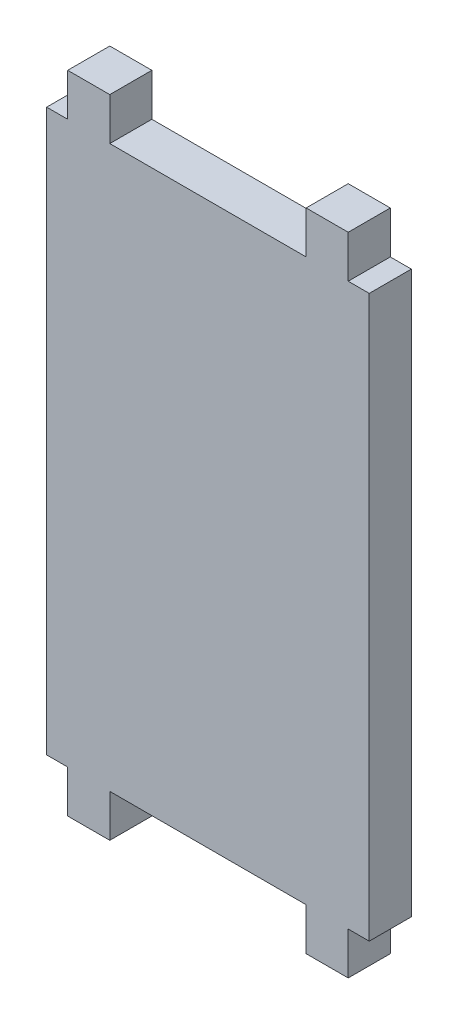
SolidWorks part; units mm, degrees
ref_plane "Alzado" through (0, 0, 0) normal (0, 0, 1) x (1, 0, 0)
ref_plane "Planta" through (0, 0, 0) normal (0, 1, 0) x (1, 0, 0)
ref_plane "Vista lateral" through (0, 0, 0) normal (1, 0, 0) x (0, 0, -1)
sketch "Model" plane through (0, 0, 0) normal (0, 0, 1) x (1, 0, 0)
  line L0 (73, 90) -> (73, 10)
  line L1 (70, 96.05) -> (70, 90)
  line L2 (30, 3.95) -> (36, 3.95)
  line L3 (64, 96.05) -> (64, 90)
  line L4 (36, 96.05) -> (36, 90)
  line L5 (30, 96.05) -> (30, 90)
  line L6 (27, 90) -> (27, 10)
  line L7 (27, 10) -> (30, 10)
  line L8 (27, 90) -> (30, 90)
  line L9 (30, 96.05) -> (36, 96.05)
  line L10 (64, 96.05) -> (70, 96.05)
  line L11 (36, 90) -> (64, 90)
  line L12 (70, 90) -> (73, 90)
  line L13 (70, 10) -> (70, 3.95)
  line L14 (64, 10) -> (64, 3.95)
  line L15 (36, 10) -> (36, 3.95)
  line L16 (30, 10) -> (30, 3.95)
  line L17 (64, 3.95) -> (70, 3.95)
  line L18 (36, 10) -> (64, 10)
  line L19 (70, 10) -> (73, 10)
extrude "Saliente-Extruir1" add sketch "Model" along normal blind 6
